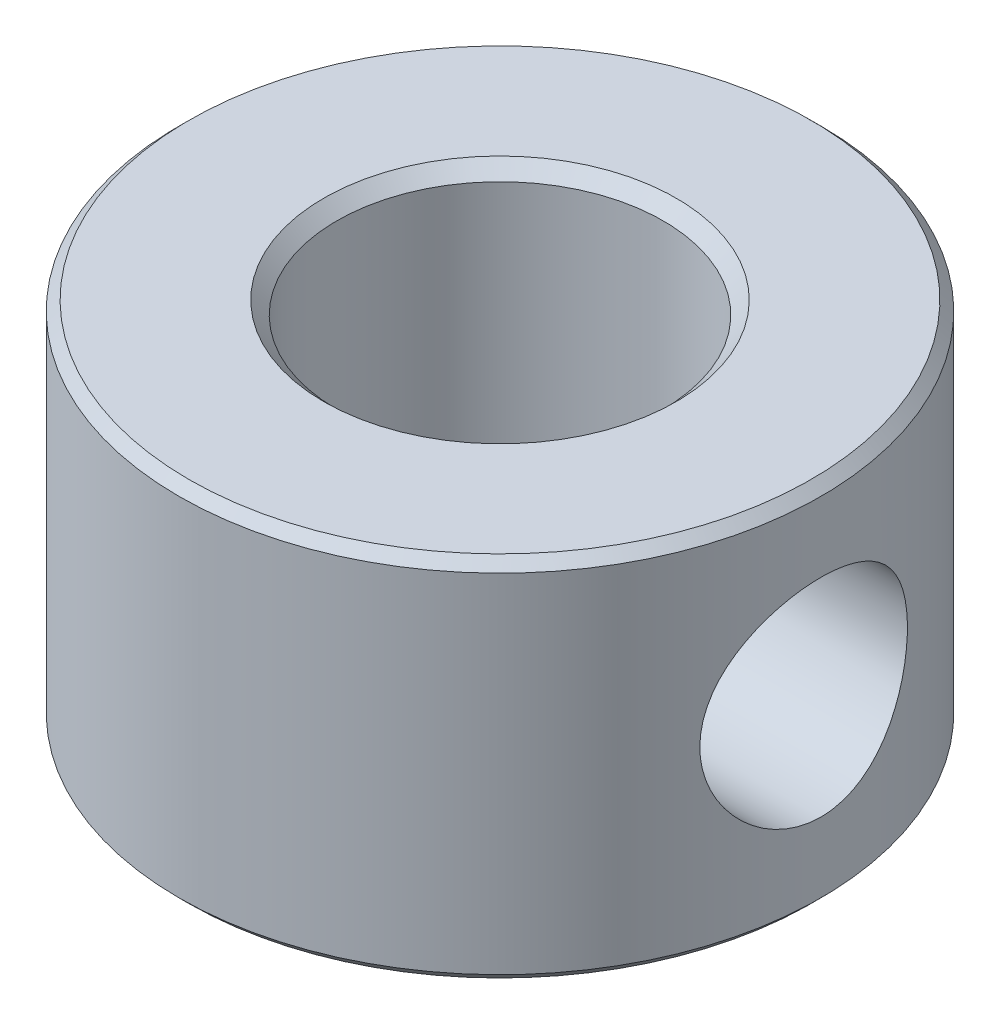
SolidWorks part; units mm, degrees
ref_plane "Front Plane" through (0, 0, 0) normal (0, 0, 1) x (1, 0, 0)
ref_plane "Top Plane" through (0, 0, 0) normal (0, 1, 0) x (1, 0, 0)
ref_plane "Right Plane" through (0, 0, 0) normal (1, 0, 0) x (0, 0, -1)
sketch "Sketch1" plane through (0, 0, 0) normal (0, 1, 0) x (1, 0, 0)
  circle A0 centre (0, 0) radius 3.175
  circle A1 centre (0, 0) radius 6.242
  dimension "D1" = 12.4841
  dimension "D2" = 6.35
extrude "Boss-Extrude1" add sketch "Sketch1" along normal blind 7.145
chamfer "Chamfer1" distance 0.1905 angle 45 2 edges at (0, 0, 6.2421) (0, 7.145, 6.2421)
chamfer "Chamfer2" distance 0.254 angle 45 2 edges at (0, 7.145, 3.175) (0, 0, 3.175)
hole_wizard "#10-32 Tapped Hole1" positions "Sketch4" profile "Sketch3" tap size "#10-32" standard "ANSI Inch"
sketch "Sketch4" plane through (0, 0, 0) normal (1, 0, 0) x (0, 0, -1)
  line L0 (0, 3.5725) -> (0, 0) construction
  line L2 (0, 3.5725) -> (6.2421, 3.5725) construction
  line L3 (6.2421, 0.1905) -> (6.2421, 6.9545) construction
  point P1 (0, 3.5725)
sketch "Sketch3" plane through (0, 3.5725, 0) normal (0, 1, 0) x (0, 0, 1)
  line L0 (0, 0) -> (0, 6.2421)
  line L1 (0, 6.2421) -> (2.0193, 6.2421)
  line L2 (2.0193, 6.2421) -> (2.0193, 0)
  line L5 (2.0193, 0) -> (0, 0)
  line L11 (0, -6.35) -> (0, 107.95) construction
  dimension "Thru Tap Drill Dia." = 4.0386
  dimension "Thru Tap Drill Depth" = 6.2421
cosmetic thread "Hole Thread1" parameters "D2"=4.826
